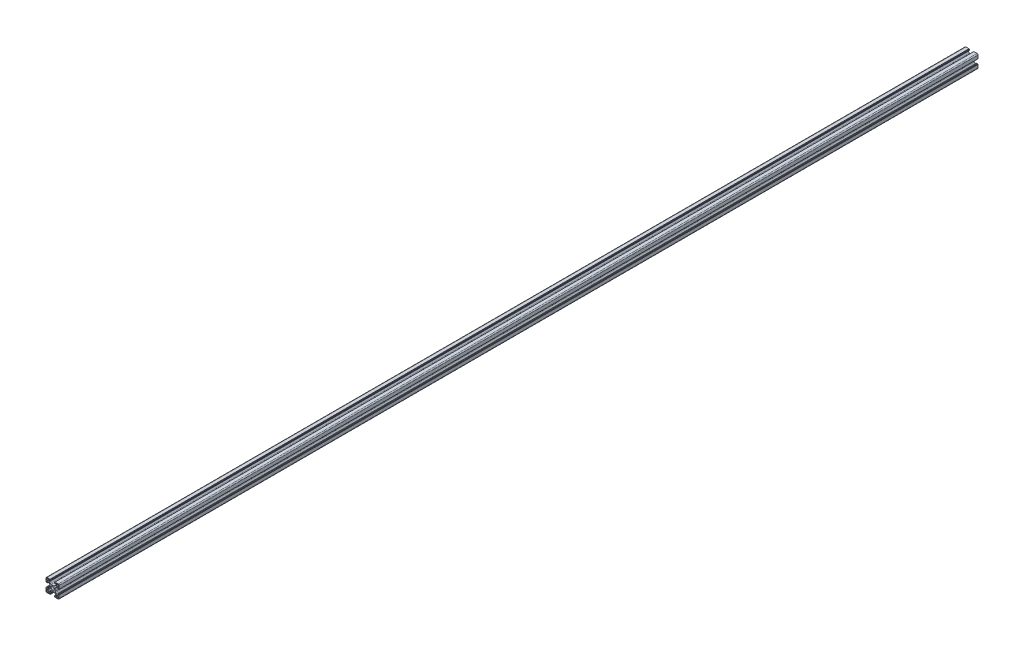
SolidWorks part; units mm, degrees
material "1060 Сплав"
ref_plane "Спереди" through (0, 0, 0) normal (0, 0, 1) x (1, 0, 0)
ref_plane "Сверху" through (0, 0, 0) normal (0, 1, 0) x (1, 0, 0)
ref_plane "Справа" through (0, 0, 0) normal (1, 0, 0) x (0, 0, -1)
sketch "Эскиз1" plane through (0, 0, 0) normal (0, 0, 1) x (1, 0, 0)
  line L0 (9.3595, 9.1357) -> (6.3595, 6.1357) construction
  line L1 (0.2595, 4.0357) -> (2.1582, 4.0357)
  line L2 (0.2595, 0.0357) -> (10.2595, 10.0357) construction
  line L3 (7.8595, 7.6357) -> (6.3595, 9.1357) construction
  line L4 (3.5725, 4.6215) -> (4.8737, 5.9227)
  line L5 (7.1595, 6.1357) -> (8.5595, 6.1357)
  line L6 (6.3595, 6.9357) -> (6.3595, 8.3357)
  line L7 (8.5595, 9.1357) -> (7.1595, 9.1357)
  line L8 (5.4595, 8.2357) -> (5.4595, 7.3369)
  line L9 (4.0227, 8.1089) -> (4.503, 8.5893)
  line L10 (3.4595, 9.5848) -> (3.9595, 9.5848)
  line L11 (3.8459, 8.0357) -> (3.5595, 8.0357)
  line L12 (4.8566, 8.7357) -> (4.9595, 8.7357)
  line L13 (3.9595, 9.8857) -> (3.9595, 9.5848)
  line L14 (3.3095, 9.4348) -> (3.3095, 8.2857)
  line L15 (8.7595, 10.0357) -> (4.1095, 10.0357)
  line L16 (9.3595, 8.3357) -> (9.3595, 6.9357)
  line L17 (10.2595, 8.5357) -> (10.2595, 3.8857)
  line L18 (9.6585, 3.0857) -> (8.5095, 3.0857)
  line L19 (10.1095, 3.7357) -> (9.8085, 3.7357)
  line L20 (8.9595, 4.6328) -> (8.9595, 4.7357)
  line L21 (8.2595, 3.6221) -> (8.2595, 3.3357)
  line L22 (9.8085, 3.2357) -> (9.8085, 3.7357)
  line L23 (8.3327, 3.7989) -> (8.813, 4.2793)
  line L24 (8.4595, 5.2357) -> (7.5607, 5.2357)
  line L25 (4.8452, 3.3487) -> (6.1465, 4.6499)
  line L26 (4.2595, 0.0357) -> (4.2595, 1.9345)
  line L27 (4.2595, 0.0357) -> (4.2595, -1.8631)
  line L28 (4.8452, -3.2773) -> (6.1465, -4.5785)
  line L29 (6.3595, -6.8643) -> (6.3595, -8.2643)
  line L30 (7.1595, -6.0643) -> (8.5595, -6.0643)
  line L31 (9.3595, -8.2643) -> (9.3595, -6.8643)
  line L32 (8.4595, -5.1643) -> (7.5607, -5.1643)
  line L33 (8.3327, -3.7275) -> (8.813, -4.2079)
  line L34 (9.8085, -3.1643) -> (9.8085, -3.6643)
  line L35 (8.2595, -3.5507) -> (8.2595, -3.2643)
  line L36 (8.9595, -4.5614) -> (8.9595, -4.6643)
  line L37 (10.1095, -3.6643) -> (9.8085, -3.6643)
  line L38 (9.6585, -3.0143) -> (8.5095, -3.0143)
  line L39 (10.2595, -8.4643) -> (10.2595, -3.8143)
  line L40 (8.5595, -9.0643) -> (7.1595, -9.0643)
  line L41 (8.7595, -9.9643) -> (4.1095, -9.9643)
  line L42 (3.3095, -9.3634) -> (3.3095, -8.2143)
  line L43 (3.9595, -9.8143) -> (3.9595, -9.5134)
  line L44 (4.8566, -8.6643) -> (4.9595, -8.6643)
  line L45 (3.8459, -7.9643) -> (3.5595, -7.9643)
  line L46 (3.4595, -9.5134) -> (3.9595, -9.5134)
  line L47 (4.0227, -8.0375) -> (4.503, -8.5179)
  line L48 (5.4595, -8.1643) -> (5.4595, -7.2655)
  line L49 (3.5725, -4.5501) -> (4.8737, -5.8513)
  line L50 (0.2595, -3.9643) -> (2.1582, -3.9643)
  line L51 (9.3595, -9.0643) -> (6.3595, -6.0643) construction
  line L52 (0.2595, 0.0357) -> (10.2595, -9.9643) construction
  line L53 (7.8595, -7.5643) -> (9.3595, -6.0643) construction
  line L54 (0.2595, -3.9643) -> (-1.6393, -3.9643)
  line L55 (-3.0535, -4.5501) -> (-4.3548, -5.8513)
  line L56 (-6.6405, -6.0643) -> (-8.0405, -6.0643)
  line L57 (-5.8405, -6.8643) -> (-5.8405, -8.2643)
  line L58 (-8.0405, -9.0643) -> (-6.6405, -9.0643)
  line L59 (-4.9405, -8.1643) -> (-4.9405, -7.2655)
  line L60 (-3.5038, -8.0375) -> (-3.9841, -8.5179)
  line L61 (-2.9405, -9.5134) -> (-3.4405, -9.5134)
  line L62 (-3.327, -7.9643) -> (-3.0405, -7.9643)
  line L63 (-4.3376, -8.6643) -> (-4.4405, -8.6643)
  line L64 (-3.4405, -9.8143) -> (-3.4405, -9.5134)
  line L65 (-2.7905, -9.3634) -> (-2.7905, -8.2143)
  line L66 (-8.2405, -9.9643) -> (-3.5905, -9.9643)
  line L67 (-8.8405, -8.2643) -> (-8.8405, -6.8643)
  line L68 (-9.7405, -8.4643) -> (-9.7405, -3.8143)
  line L69 (-9.1396, -3.0143) -> (-7.9905, -3.0143)
  line L70 (-9.5905, -3.6643) -> (-9.2896, -3.6643)
  line L71 (-8.4405, -4.5614) -> (-8.4405, -4.6643)
  line L72 (-7.7405, -3.5507) -> (-7.7405, -3.2643)
  line L73 (-9.2896, -3.1643) -> (-9.2896, -3.6643)
  line L74 (-7.8138, -3.7275) -> (-8.2941, -4.2079)
  line L75 (-7.9405, -5.1643) -> (-7.0418, -5.1643)
  line L76 (-4.3263, -3.2773) -> (-5.6275, -4.5785)
  line L77 (-3.7405, 0.0357) -> (-3.7405, -1.8631)
  line L78 (-8.8405, -9.0643) -> (-5.8405, -6.0643) construction
  line L79 (0.2595, 0.0357) -> (-9.7405, -9.9643) construction
  line L80 (-7.3405, -7.5643) -> (-5.8405, -9.0643) construction
  line L81 (-3.7405, 0.0357) -> (-3.7405, 1.9345)
  line L82 (-4.3263, 3.3487) -> (-5.6275, 4.6499)
  line L83 (-5.8405, 6.9357) -> (-5.8405, 8.3357)
  line L84 (-6.6405, 6.1357) -> (-8.0405, 6.1357)
  line L85 (-8.8405, 8.3357) -> (-8.8405, 6.9357)
  line L86 (-7.9405, 5.2357) -> (-7.0418, 5.2357)
  line L87 (-7.8138, 3.7989) -> (-8.2941, 4.2793)
  line L88 (-9.2896, 3.2357) -> (-9.2896, 3.7357)
  line L89 (-7.7405, 3.6221) -> (-7.7405, 3.3357)
  line L90 (-8.4405, 4.6328) -> (-8.4405, 4.7357)
  line L91 (-9.5905, 3.7357) -> (-9.2896, 3.7357)
  line L92 (-9.1396, 3.0857) -> (-7.9905, 3.0857)
  line L93 (-9.7405, 8.5357) -> (-9.7405, 3.8857)
  line L94 (-8.0405, 9.1357) -> (-6.6405, 9.1357)
  line L95 (-8.2405, 10.0357) -> (-3.5905, 10.0357)
  line L96 (-2.7905, 9.4348) -> (-2.7905, 8.2857)
  line L97 (-3.4405, 9.8857) -> (-3.4405, 9.5848)
  line L98 (-4.3376, 8.7357) -> (-4.4405, 8.7357)
  line L99 (-3.327, 8.0357) -> (-3.0405, 8.0357)
  line L100 (-2.9405, 9.5848) -> (-3.4405, 9.5848)
  line L101 (-3.5038, 8.1089) -> (-3.9841, 8.5893)
  line L102 (-4.9405, 8.2357) -> (-4.9405, 7.3369)
  line L103 (-3.0535, 4.6215) -> (-4.3548, 5.9227)
  line L104 (0.2595, 4.0357) -> (-1.6393, 4.0357)
  line L105 (-11.5046, 0.0357) -> (11.7638, 0.0357) construction
  line L106 (-8.8405, 9.1357) -> (-5.8405, 6.1357) construction
  line L107 (0.2595, -12.0507) -> (0.2595, 10.7546) construction
  line L108 (0.2595, 0.0357) -> (-9.7405, 10.0357) construction
  line L109 (-7.3405, 7.6357) -> (-8.8405, 6.1357) construction
  arc A0 (9.3595, 8.3357) -> (8.5595, 9.1357) centre (8.5595, 8.3357) ccw
  arc A1 (7.1595, 9.1357) -> (6.3595, 8.3357) centre (7.1595, 8.3357) ccw
  arc A2 (7.1595, 6.1357) -> (6.3595, 6.9357) centre (7.1595, 6.9357) cw
  arc A3 (8.7595, 10.0357) -> (10.2595, 8.5357) centre (8.7595, 8.5357) cw
  arc A4 (3.4595, 9.5848) -> (3.3095, 9.4348) centre (3.4595, 9.4348) ccw
  arc A5 (4.1095, 10.0357) -> (3.9595, 9.8857) centre (4.1095, 9.8857) ccw
  arc A6 (3.8459, 8.0357) -> (4.0227, 8.1089) centre (3.8459, 8.2857) ccw
  arc A7 (3.5595, 8.0357) -> (3.3095, 8.2857) centre (3.5595, 8.2857) cw
  arc A8 (4.503, 8.5893) -> (4.8566, 8.7357) centre (4.8566, 8.2357) cw
  arc A9 (4.9595, 8.7357) -> (5.4595, 8.2357) centre (4.9595, 8.2357) cw
  arc A10 (2.7595, 0.0357) -> (0.2595, 2.5357) centre (0.2595, 0.0357) ccw
  arc A11 (2.1582, 4.0357) -> (3.5725, 4.6215) centre (2.1582, 6.0357) ccw
  arc A12 (5.4595, 7.3369) -> (4.8737, 5.9227) centre (3.4595, 7.3369) cw
  arc A13 (9.3595, 6.9357) -> (8.5595, 6.1357) centre (8.5595, 6.9357) cw
  arc A14 (8.9595, 4.7357) -> (8.4595, 5.2357) centre (8.4595, 4.7357) ccw
  arc A15 (8.813, 4.2793) -> (8.9595, 4.6328) centre (8.4595, 4.6328) ccw
  arc A16 (8.2595, 3.3357) -> (8.5095, 3.0857) centre (8.5095, 3.3357) ccw
  arc A17 (8.2595, 3.6221) -> (8.3327, 3.7989) centre (8.5095, 3.6221) cw
  arc A18 (10.2595, 3.8857) -> (10.1095, 3.7357) centre (10.1095, 3.8857) cw
  arc A19 (9.8085, 3.2357) -> (9.6585, 3.0857) centre (9.6585, 3.2357) cw
  arc A20 (7.5607, 5.2357) -> (6.1465, 4.6499) centre (7.5607, 3.2357) ccw
  arc A21 (4.2595, 1.9345) -> (4.8452, 3.3487) centre (6.2595, 1.9345) cw
  arc A22 (8.5595, -9.0643) -> (9.3595, -8.2643) centre (8.5595, -8.2643) ccw
  arc A23 (9.3595, -6.8643) -> (8.5595, -6.0643) centre (8.5595, -6.8643) ccw
  arc A24 (6.3595, -6.8643) -> (7.1595, -6.0643) centre (7.1595, -6.8643) cw
  arc A25 (10.2595, -8.4643) -> (8.7595, -9.9643) centre (8.7595, -8.4643) cw
  arc A26 (9.8085, -3.1643) -> (9.6585, -3.0143) centre (9.6585, -3.1643) ccw
  arc A27 (10.2595, -3.8143) -> (10.1095, -3.6643) centre (10.1095, -3.8143) ccw
  arc A28 (8.2595, -3.5507) -> (8.3327, -3.7275) centre (8.5095, -3.5507) ccw
  arc A29 (8.2595, -3.2643) -> (8.5095, -3.0143) centre (8.5095, -3.2643) cw
  arc A30 (8.813, -4.2079) -> (8.9595, -4.5614) centre (8.4595, -4.5614) cw
  arc A31 (8.9595, -4.6643) -> (8.4595, -5.1643) centre (8.4595, -4.6643) cw
  arc A32 (0.2595, -2.4643) -> (2.7595, 0.0357) centre (0.2595, 0.0357) ccw
  arc A33 (4.2595, -1.8631) -> (4.8452, -3.2773) centre (6.2595, -1.8631) ccw
  arc A34 (7.5607, -5.1643) -> (6.1465, -4.5785) centre (7.5607, -3.1643) cw
  arc A35 (7.1595, -9.0643) -> (6.3595, -8.2643) centre (7.1595, -8.2643) cw
  arc A36 (4.9595, -8.6643) -> (5.4595, -8.1643) centre (4.9595, -8.1643) ccw
  arc A37 (4.503, -8.5179) -> (4.8566, -8.6643) centre (4.8566, -8.1643) ccw
  arc A38 (3.5595, -7.9643) -> (3.3095, -8.2143) centre (3.5595, -8.2143) ccw
  arc A39 (3.8459, -7.9643) -> (4.0227, -8.0375) centre (3.8459, -8.2143) cw
  arc A40 (4.1095, -9.9643) -> (3.9595, -9.8143) centre (4.1095, -9.8143) cw
  arc A41 (3.4595, -9.5134) -> (3.3095, -9.3634) centre (3.4595, -9.3634) cw
  arc A42 (5.4595, -7.2655) -> (4.8737, -5.8513) centre (3.4595, -7.2655) ccw
  arc A43 (2.1582, -3.9643) -> (3.5725, -4.5501) centre (2.1582, -5.9643) cw
  arc A44 (-8.8405, -8.2643) -> (-8.0405, -9.0643) centre (-8.0405, -8.2643) ccw
  arc A45 (-6.6405, -9.0643) -> (-5.8405, -8.2643) centre (-6.6405, -8.2643) ccw
  arc A46 (-6.6405, -6.0643) -> (-5.8405, -6.8643) centre (-6.6405, -6.8643) cw
  arc A47 (-8.2405, -9.9643) -> (-9.7405, -8.4643) centre (-8.2405, -8.4643) cw
  arc A48 (-2.9405, -9.5134) -> (-2.7905, -9.3634) centre (-2.9405, -9.3634) ccw
  arc A49 (-3.5905, -9.9643) -> (-3.4405, -9.8143) centre (-3.5905, -9.8143) ccw
  arc A50 (-3.327, -7.9643) -> (-3.5038, -8.0375) centre (-3.327, -8.2143) ccw
  arc A51 (-3.0405, -7.9643) -> (-2.7905, -8.2143) centre (-3.0405, -8.2143) cw
  arc A52 (-3.9841, -8.5179) -> (-4.3376, -8.6643) centre (-4.3376, -8.1643) cw
  arc A53 (-4.4405, -8.6643) -> (-4.9405, -8.1643) centre (-4.4405, -8.1643) cw
  arc A54 (-2.2405, 0.0357) -> (0.2595, -2.4643) centre (0.2595, 0.0357) ccw
  arc A55 (-1.6393, -3.9643) -> (-3.0535, -4.5501) centre (-1.6393, -5.9643) ccw
  arc A56 (-4.9405, -7.2655) -> (-4.3548, -5.8513) centre (-2.9405, -7.2655) cw
  arc A57 (-8.8405, -6.8643) -> (-8.0405, -6.0643) centre (-8.0405, -6.8643) cw
  arc A58 (-8.4405, -4.6643) -> (-7.9405, -5.1643) centre (-7.9405, -4.6643) ccw
  arc A59 (-8.2941, -4.2079) -> (-8.4405, -4.5614) centre (-7.9405, -4.5614) ccw
  arc A60 (-7.7405, -3.2643) -> (-7.9905, -3.0143) centre (-7.9905, -3.2643) ccw
  arc A61 (-7.7405, -3.5507) -> (-7.8138, -3.7275) centre (-7.9905, -3.5507) cw
  arc A62 (-9.7405, -3.8143) -> (-9.5905, -3.6643) centre (-9.5905, -3.8143) cw
  arc A63 (-9.2896, -3.1643) -> (-9.1396, -3.0143) centre (-9.1396, -3.1643) cw
  arc A64 (-7.0418, -5.1643) -> (-5.6275, -4.5785) centre (-7.0418, -3.1643) ccw
  arc A65 (-3.7405, -1.8631) -> (-4.3263, -3.2773) centre (-5.7405, -1.8631) cw
  arc A66 (-8.0405, 9.1357) -> (-8.8405, 8.3357) centre (-8.0405, 8.3357) ccw
  arc A67 (-8.8405, 6.9357) -> (-8.0405, 6.1357) centre (-8.0405, 6.9357) ccw
  arc A68 (-5.8405, 6.9357) -> (-6.6405, 6.1357) centre (-6.6405, 6.9357) cw
  arc A69 (-9.7405, 8.5357) -> (-8.2405, 10.0357) centre (-8.2405, 8.5357) cw
  arc A70 (-9.2896, 3.2357) -> (-9.1396, 3.0857) centre (-9.1396, 3.2357) ccw
  arc A71 (-9.7405, 3.8857) -> (-9.5905, 3.7357) centre (-9.5905, 3.8857) ccw
  arc A72 (-7.7405, 3.6221) -> (-7.8138, 3.7989) centre (-7.9905, 3.6221) ccw
  arc A73 (-7.7405, 3.3357) -> (-7.9905, 3.0857) centre (-7.9905, 3.3357) cw
  arc A74 (-8.2941, 4.2793) -> (-8.4405, 4.6328) centre (-7.9405, 4.6328) cw
  arc A75 (-8.4405, 4.7357) -> (-7.9405, 5.2357) centre (-7.9405, 4.7357) cw
  arc A76 (0.2595, 2.5357) -> (-2.2405, 0.0357) centre (0.2595, 0.0357) ccw
  arc A77 (-3.7405, 1.9345) -> (-4.3263, 3.3487) centre (-5.7405, 1.9345) ccw
  arc A78 (-7.0418, 5.2357) -> (-5.6275, 4.6499) centre (-7.0418, 3.2357) cw
  arc A79 (-6.6405, 9.1357) -> (-5.8405, 8.3357) centre (-6.6405, 8.3357) cw
  arc A80 (-4.4405, 8.7357) -> (-4.9405, 8.2357) centre (-4.4405, 8.2357) ccw
  arc A81 (-3.9841, 8.5893) -> (-4.3376, 8.7357) centre (-4.3376, 8.2357) ccw
  arc A82 (-3.0405, 8.0357) -> (-2.7905, 8.2857) centre (-3.0405, 8.2857) ccw
  arc A83 (-3.327, 8.0357) -> (-3.5038, 8.1089) centre (-3.327, 8.2857) cw
  arc A84 (-3.5905, 10.0357) -> (-3.4405, 9.8857) centre (-3.5905, 9.8857) cw
  arc A85 (-2.9405, 9.5848) -> (-2.7905, 9.4348) centre (-2.9405, 9.4348) cw
  arc A86 (-4.9405, 7.3369) -> (-4.3548, 5.9227) centre (-2.9405, 7.3369) ccw
  arc A87 (-1.6393, 4.0357) -> (-3.0535, 4.6215) centre (-1.6393, 6.0357) cw
  point P0 (0.2595, 0.0357)
  point P9 (0.2595, 0.0357)
  point P40 (8.9595, 3.7357)
  point P93 (3.9595, -8.6643)
  point P144 (3.9595, 8.7357)
  point P152 (8.9595, -3.6643)
  point P153 (0.2595, -3.8886)
  point P154 (0.2595, 0.0357)
  point P189 (-8.4405, -3.6643)
  point P228 (-3.4405, -8.6643)
  point P229 (-3.6648, 0.0357)
  point P230 (0.2595, 0.0357)
  point P268 (-3.4405, 8.7357)
  point P273 (4.1837, 0.0357)
  point P306 (-8.4405, 3.7357)
  point P307 (0.2595, 3.96)
  point P309 (0.2595, 0.0357)
  dimension "D3" = 5
  dimension "D6" = 2
  dimension "D1" = 2
  dimension "D2" = 6
  dimension "D4" = 4
  dimension "D5" = 0.9
extrude "Бобышка-Вытянуть1" add sketch "Эскиз1" along normal blind 1400
